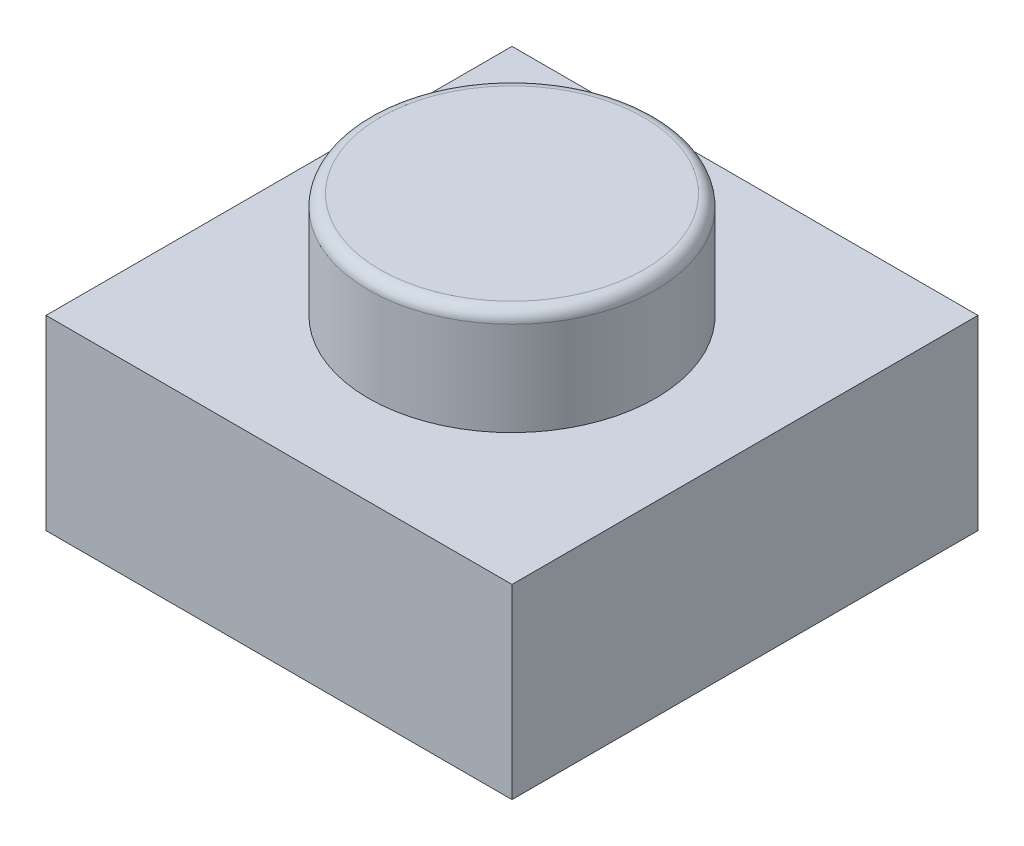
SolidWorks part; units mm, degrees
ref_plane "前视基准面" through (0, 0, 0) normal (0, 0, 1) x (1, 0, 0)
ref_plane "上视基准面" through (0, 0, 0) normal (0, 1, 0) x (1, 0, 0)
ref_plane "右视基准面" through (0, 0, 0) normal (1, 0, 0) x (0, 0, -1)
sketch "草图1" plane through (0, 0, 0) normal (0, 1, 0) x (1, 0, 0)
  line L1 (23.6676, 17.3289) -> (31.6176, 17.3289)
  line L2 (23.6676, 17.3289) -> (23.6676, 9.3789)
  line L3 (23.6676, 9.3789) -> (31.6176, 9.3789)
  line L4 (31.6176, 17.3289) -> (31.6176, 9.3789)
  dimension "D1" = 7.95
  dimension "D2" = 7.95
extrude "凸台-拉伸1" add sketch "草图1" along normal blind 3.18 contours L2 L3 L4 L1
sketch "草图2" plane through (0, 3.18, 0) normal (0, 1, 0) x (1, 0, 0)
  line L0 (23.6676, 9.3789) -> (31.6176, 9.3789) construction
  line L1 (31.6176, 17.3289) -> (31.6176, 9.3789) construction
  circle A0 centre (27.6426, 13.3539) radius 2.45
  point P2 (0, 0)
  point P5 (27.6426, 9.3789)
  point P8 (31.6176, 13.3539)
  dimension "D1" = 4.9
extrude "凸台-拉伸2" add sketch "草图2" along normal blind 1.8
fillet "圆角1" radius 0.2 1 edges at (27.6426, 4.98, -10.9039)
